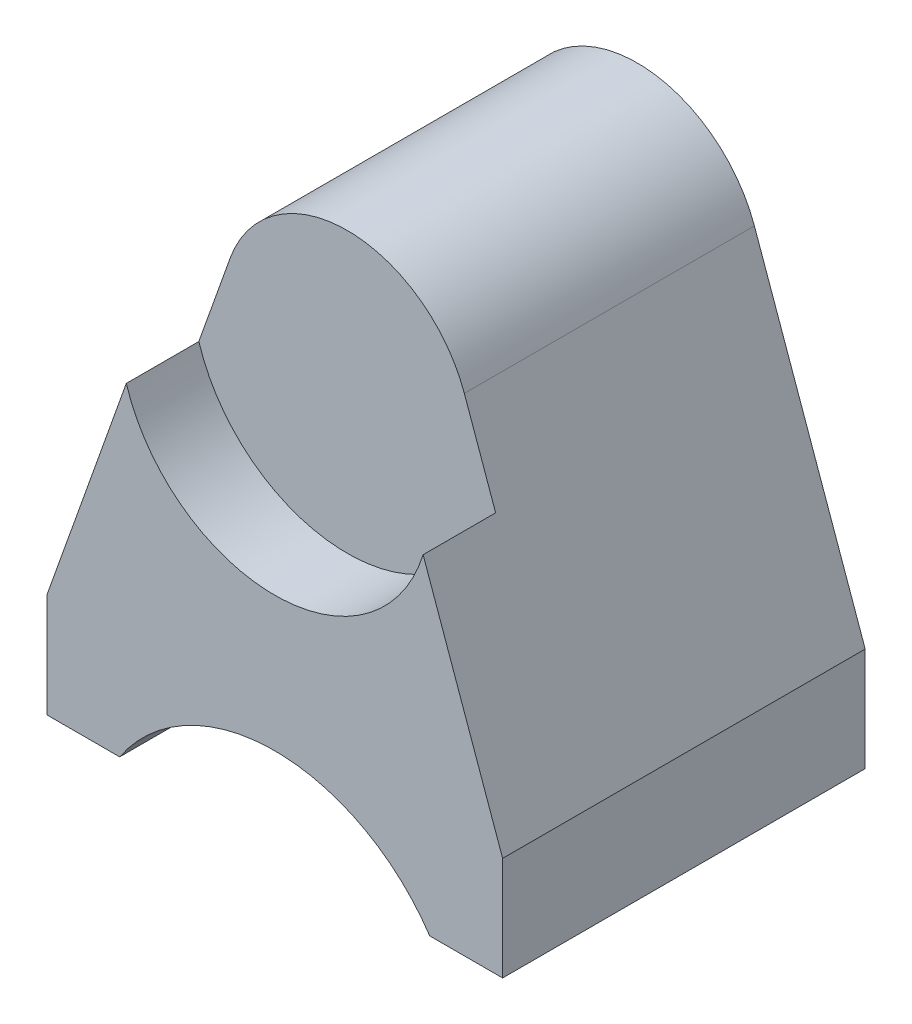
SolidWorks part; units mm, degrees
material "ABS"
ref_plane "Alzado" through (0, 0, 0) normal (0, 0, 1) x (1, 0, 0)
ref_plane "Planta" through (0, 0, 0) normal (0, 1, 0) x (1, 0, 0)
ref_plane "Vista lateral" through (0, 0, 0) normal (1, 0, 0) x (0, 0, -1)
sketch "Croquis1" plane through (0, 0, 0) normal (0, 0, 1) x (1, 0, 0)
  line L0 (0, 0) -> (0, 42.3668) construction
  line L1 (-14.9666, 0) -> (-22, 0)
  line L2 (14.9666, 0) -> (22, 0)
  line L3 (-22, 0) -> (-22, 10)
  line L4 (22, 0) -> (22, 10)
  line L5 (-22, 10) -> (-11.3042, 40.0267)
  line L6 (22, 10) -> (11.3042, 40.0267)
  arc A0 (-14.9666, 0) -> (14.9666, 0) centre (0, -10) cw
  arc A1 (-11.3042, 40.0267) -> (11.3042, 40.0267) centre (0, 36) cw
  point P13 (0, 71.7616)
  dimension "D2" = 18
  dimension "D5" = 12
  dimension "D1" = 44
  dimension "D3" = 10
  dimension "D4" = 10
  dimension "D6" = 46
extrude "Saliente-Extruir1" add sketch "Croquis1" along normal mid plane 35
sketch "Croquis2" plane through (0, 0, 17.5) normal (0, 0, 1) x (1, 0, 0)
  circle A0 centre (0, 36) radius 15
  dimension "D1" = 15
extrude "Cortar-Extruir1" cut sketch "Croquis2" against normal blind 7
